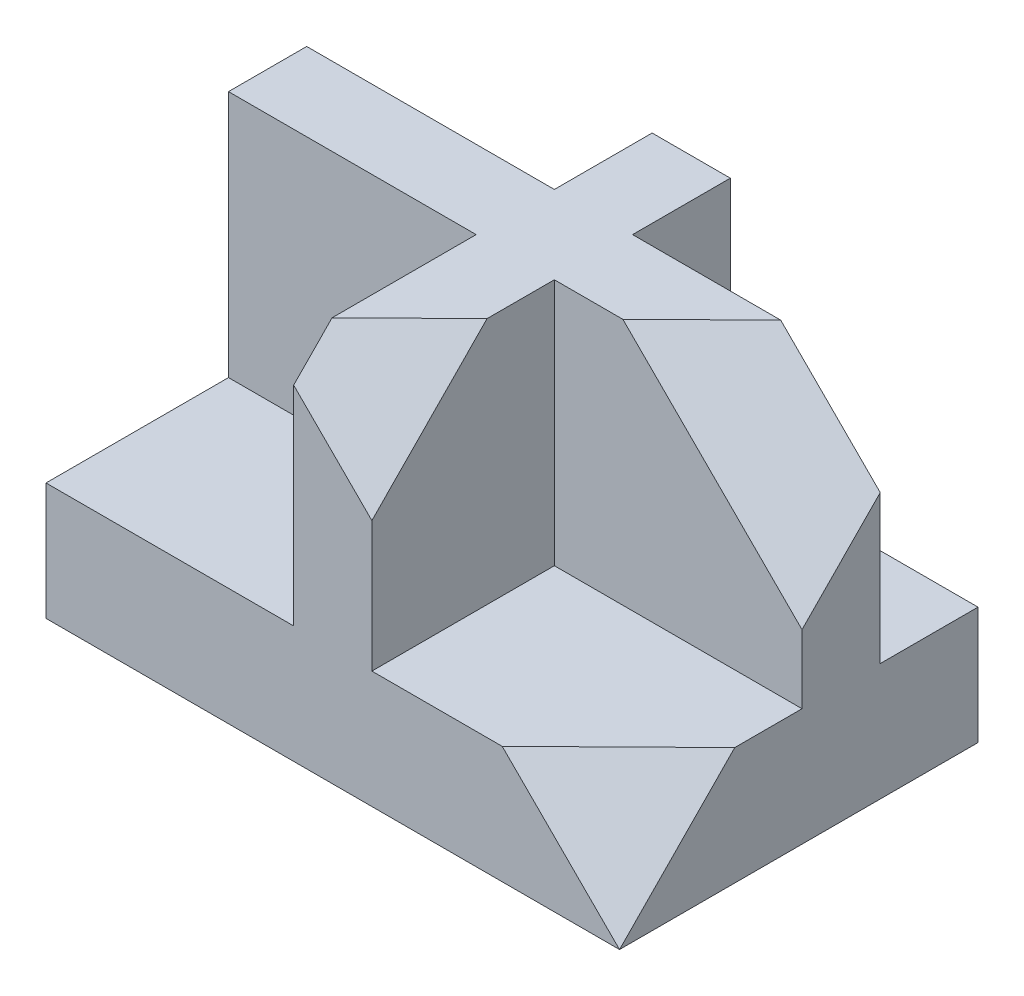
SolidWorks part; units mm, degrees
ref_plane "Front Plane" through (0, 0, 0) normal (0, 0, 1) x (1, 0, 0)
ref_plane "Top Plane" through (0, 0, 0) normal (0, 1, 0) x (1, 0, 0)
ref_plane "Right Plane" through (0, 0, 0) normal (1, 0, 0) x (0, 0, -1)
sketch "Sketch1" plane through (0, 0, 0) normal (0, 1, 0) x (1, 0, 0)
  line L0 (-44, 0) -> (0, 0) construction
  line L1 (-44, 27.5) -> (44, 27.5)
  line L2 (-44, 27.5) -> (-44, -27.5)
  line L3 (-44, -27.5) -> (44, -27.5)
  line L4 (44, 27.5) -> (44, -27.5)
  line L5 (0, 0) -> (0, 27.5) construction
  dimension "D1" = 55
  dimension "D2" = 88
extrude "Boss-Extrude1" add sketch "Sketch1" along normal blind 18 contours L2 L3 L4 L1
sketch "Sketch2" plane through (0, 18, 0) normal (0, 1, 0) x (1, 0, 0)
  line L0 (-6, 27.5) -> (-6, 12.5)
  line L1 (-44, 27.5) -> (44, 27.5) construction
  line L2 (-6, 12.5) -> (-44, 12.5)
  line L3 (-44, 27.5) -> (-44, -27.5) construction
  line L4 (-44, 12.5) -> (-44, 0.5)
  line L5 (-44, 0.5) -> (-6, 0.5)
  line L6 (-6, 0.5) -> (-6, -27.5)
  line L7 (-44, -27.5) -> (44, -27.5) construction
  line L8 (-6, -27.5) -> (6, -27.5)
  line L9 (6, -27.5) -> (6, 0.5)
  line L10 (6, 0.5) -> (44, 0.5)
  line L11 (44, 27.5) -> (44, -27.5) construction
  line L12 (44, 0.5) -> (44, 12.5)
  line L13 (44, 12.5) -> (6, 12.5)
  line L14 (6, 12.5) -> (6, 27.5)
  line L15 (6, 27.5) -> (-6, 27.5)
  line L16 (6, 0.5) -> (64.875, 0.5) construction
  line L17 (6, -27.5) -> (64.875, -27.5) construction
  line L19 (-6, 0.5) -> (-78.9519, 0.5) construction
  line L20 (-6, -27.5) -> (-82.2397, -27.5) construction
  dimension "D1" = 12
  dimension "D2" = 12
  dimension "D3" = 12
  dimension "D4" = 12
  dimension "D5" = 28
  dimension "D6" = 28
  dimension "D7" = 38
  dimension "D8" = 38
extrude "Boss-Extrude2" add sketch "Sketch2" along normal blind 38
sketch "Sketch3" plane through (0, 56, 0) normal (0, 1, 0) x (1, 0, 0)
  line L1 (-44, 27.5) -> (44, 27.5) construction
  line L2 (-44, 27.5) -> (-44, -27.5) construction
  line L3 (-44, -27.5) -> (44, -27.5) construction
  line L4 (44, 27.5) -> (44, -27.5) construction
  line L5 (-44, 27.5) -> (44, -27.5) construction
  line L6 (-44, -27.5) -> (44, 27.5) construction
  point P0 (0, 0)
sketch "Sketch4" plane through (0, 0, 27.5) normal (0, 0, 1) x (1, 0, 0)
  line L0 (44, 0) -> (-12, 56) construction
  line L1 (-44, 56) -> (44, 56) construction
  line L2 (-44, 0) -> (44, 0) construction
  dimension "D1" = 45
ref_plane "Plane1" through (23.71, 23.71, 24.1411) normal (-0.5739, -0.5739, -0.5843) x (-0.819, 0.4021, 0.4094)
sketch "Sketch6" plane through (23.71, 23.71, 24.1411) normal (-0.5739, -0.5739, -0.5843) x (-0.819, 0.4021, 0.4094)
  line L0 (-24.7754, -19.2695) -> (43.6041, 20.6836)
  line L1 (43.6041, 20.6836) -> (-24.7754, 59.2226)
  line L2 (-24.7754, 59.2226) -> (-24.7754, -19.2695)
extrude "Cut-Extrude4" cut sketch "Sketch6" against normal blind 38
